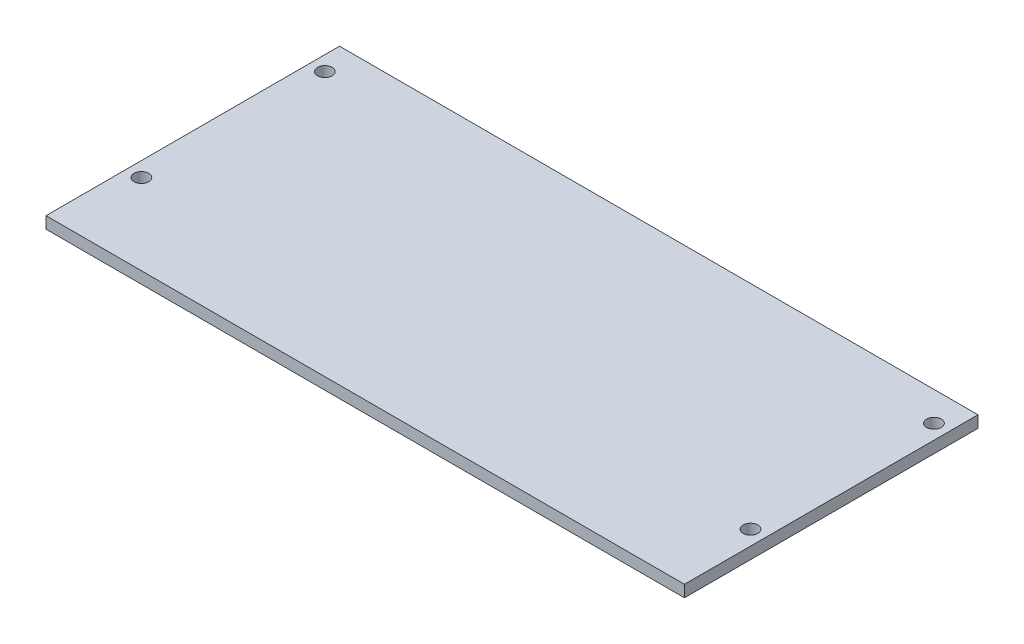
SolidWorks part; units mm, degrees
ref_plane "Front Plane" through (0, 0, 0) normal (0, 0, 1) x (1, 0, 0)
ref_plane "Top Plane" through (0, 0, 0) normal (0, 1, 0) x (1, 0, 0)
ref_plane "Right Plane" through (0, 0, 0) normal (1, 0, 0) x (0, 0, -1)
sketch "Sketch1" plane through (0, 0, 0) normal (0, 1, 0) x (1, 0, 0)
  line L1 (0, 0) -> (87, 0)
  line L2 (0, 0) -> (0, 40)
  line L3 (0, 40) -> (87, 40)
  line L4 (87, 0) -> (87, 40)
  dimension "D1" = 87
  dimension "D2" = 40
extrude "Boss-Extrude1" add sketch "Sketch1" along normal blind 1.6
sketch "Sketch2" plane through (0, 1.6, 0) normal (0, 1, 0) x (1, 0, 0)
  line L0 (0, 40) -> (0, 0) construction
  line L1 (0, 0) -> (87, 0) construction
  circle A0 centre (2, 11) radius 1
  circle A1 centre (2, 36) radius 1
  circle A2 centre (85, 36) radius 1
  circle A3 centre (85, 11) radius 1
  dimension "D1" = 2
  dimension "D2" = 2
  dimension "D3" = 11
  dimension "D4" = 36
  dimension "D5" = 85
extrude "Cut-Extrude1" cut sketch "Sketch2" against normal through all
